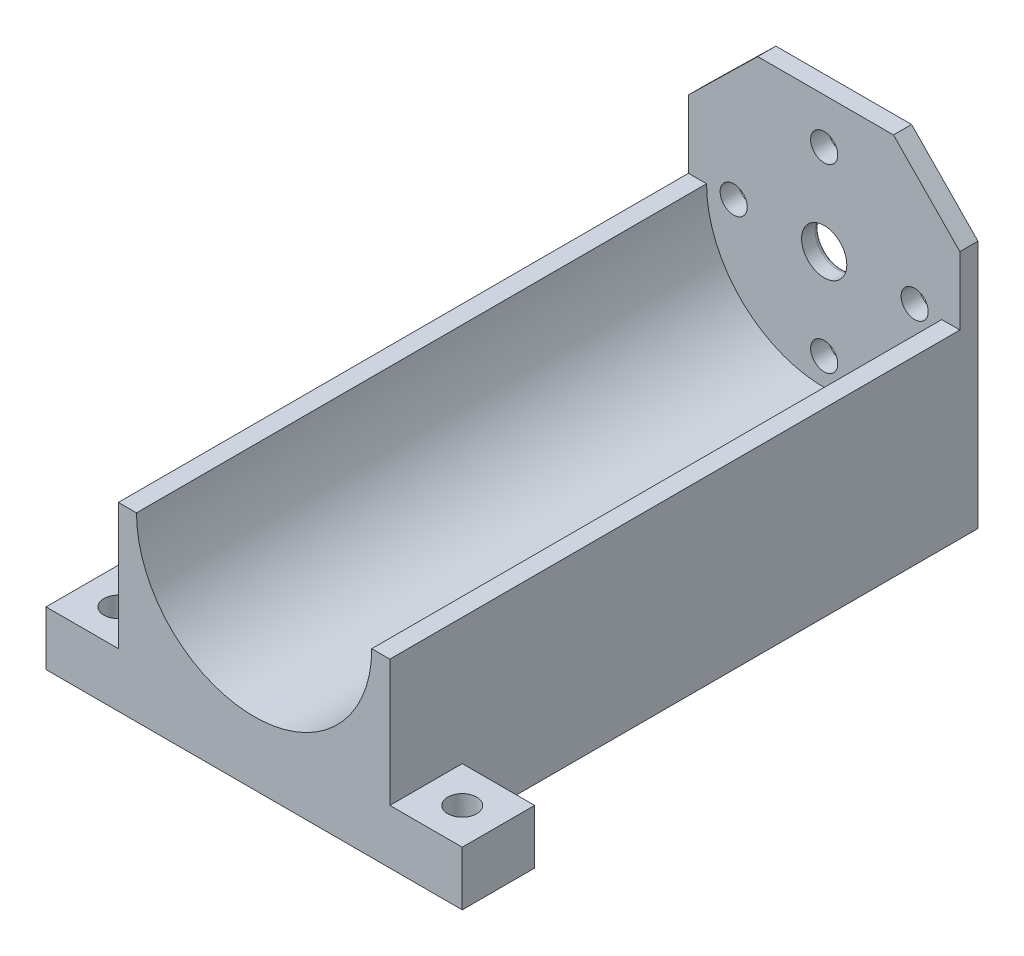
SolidWorks part; units mm, degrees
ref_plane "Plan de face" through (0, 0, 0) normal (0, 0, 1) x (1, 0, 0)
ref_plane "Plan de dessus" through (0, 0, 0) normal (0, 1, 0) x (1, 0, 0)
ref_plane "Plan de droite" through (0, 0, 0) normal (1, 0, 0) x (0, 0, -1)
sketch "Esquisse1" plane through (0, 0, 0) normal (0, 0, 1) x (1, 0, 0)
  line L0 (0, 0) -> (0, 10) construction
  line L1 (0, 0) -> (10, 0) construction
  line L2 (0, 0) -> (0, -10) construction
  line L3 (0, 0) -> (-10, 0) construction
  line L4 (-15, 0) -> (-15, 15)
  line L5 (-15, 15) -> (15, 15)
  line L6 (15, 15) -> (15, 0)
  line L7 (-15, 0) -> (-13, 0)
  line L8 (15, 0) -> (13, 0)
  line L9 (-15, 15) -> (-15, 0)
  line L10 (-15, 15) -> (0.318, 15)
  line L11 (-15, 15) -> (-15, 0)
  line L12 (-15, 7.5) -> (-15, 15)
  line L13 (-15, 15) -> (-7.341, 15)
  line L14 (-15, 7.5) -> (-7.341, 15)
  line L15 (15, 15) -> (15, 0)
  line L16 (15, 7.5) -> (15, 15)
  line L17 (0.318, 15) -> (15, 15)
  line L18 (7.659, 15) -> (15, 15)
  line L19 (7.659, 15) -> (15, 7.5)
  circle A0 centre (0, 0) radius 13
  circle A1 centre (0, 0) radius 15
  circle A2 centre (0, 10) radius 1.5
  circle A3 centre (-10, 0) radius 1.5
  circle A4 centre (10, 0) radius 1.5
  circle A5 centre (0, -10) radius 1.5
  circle A6 centre (0, 0) radius 2.5
  arc A7 (-13, 0) -> (13, 0) centre (0, 0) cw
extrude "Boss.-Extru.1" add sketch "Esquisse1" along normal blind 2 contours A0 A6 A5 A4 A3 A2 | L8 A1 L7 A0 | A1 L5 L4 | A1 L6 L5
sketch "Esquisse2" plane through (0, 0, 0) normal (0, 0, -1) x (-1, 0, 0)
  line L0 (0, 0) -> (0, -20) construction
  line L1 (0, -20) -> (15, -20)
  line L2 (15, -20) -> (15, 0)
  line L3 (0, -20) -> (-15, -20)
  line L4 (-15, -20) -> (-15, 0)
  line L5 (-15, 0) -> (-13, 0)
  line L6 (15, 0) -> (13, 0)
  line L7 (-15, 0) -> (-15, 15)
  line L8 (-15, 15) -> (15, 15)
  line L9 (15, 15) -> (15, 0)
  circle A0 centre (0, 0) radius 15
  circle A1 centre (0, 0) radius 13 construction
  circle A2 centre (0, 0) radius 13
  arc M7 (-13, 0) -> (13, 0) centre (0, 0) ccw
  line M21 (13, 0) -> (15, 0)
  line M25 (-15, 0) -> (-13, 0)
extrude "Boss.-Extru.2" add sketch "Esquisse2" against normal blind 65 contours A2 L0 A0 M21 | L0 A0 M7 M25 | L0 A0 L4 L3 | A0 L0 L1 L2
fillet "Congé1" radius 0.5 1 edges at (2.5, 0, 0)
sketch "Esquisse3" plane through (0, -20, 0) normal (0, -1, 0) x (1, 0, 0)
  line L3 (-23, 8) -> (-15, 0) construction
  line L20 (-15, 0) -> (-23, 0)
  line L21 (-23, 0) -> (-23, 8)
  line L22 (-23, 8) -> (-15, 8)
  line L23 (-15, 65) -> (-15, 0) construction
  line L24 (-15, 8) -> (-15, 0)
  line L25 (-15, 8) -> (-15, 16)
  line L26 (-15, 16) -> (-23, 16)
  line L27 (-23, 16) -> (-23, 8)
  line L28 (-23, 0) -> (-15, 8) construction
  line L29 (-23, 16) -> (-15, 8) construction
  line L30 (-23, 8) -> (-15, 16) construction
  line L36 (-15, 65) -> (-23, 65)
  line L37 (-23, 65) -> (-23, 57)
  line L38 (-23, 57) -> (-15, 57)
  line L39 (-15, 57) -> (-15, 65)
  line L40 (-23, 65) -> (-15, 57) construction
  line L41 (-15, 65) -> (-23, 57) construction
  line L42 (15, 65) -> (23, 65)
  line L43 (23, 65) -> (23, 57)
  line L44 (23, 57) -> (15, 57)
  line L45 (15, 65) -> (15, 0) construction
  line L46 (15, 57) -> (15, 65)
  line L47 (23, 57) -> (15, 65) construction
  line L48 (23, 65) -> (15, 57) construction
  circle A2 centre (-19, 12) radius 1.6
  circle A3 centre (-19, 4) radius 1.6
  circle A6 centre (19, 61) radius 1.6
  circle A7 centre (-19, 61) radius 1.6
extrude "Boss.-Extru.4" add sketch "Esquisse3" against normal blind 6
